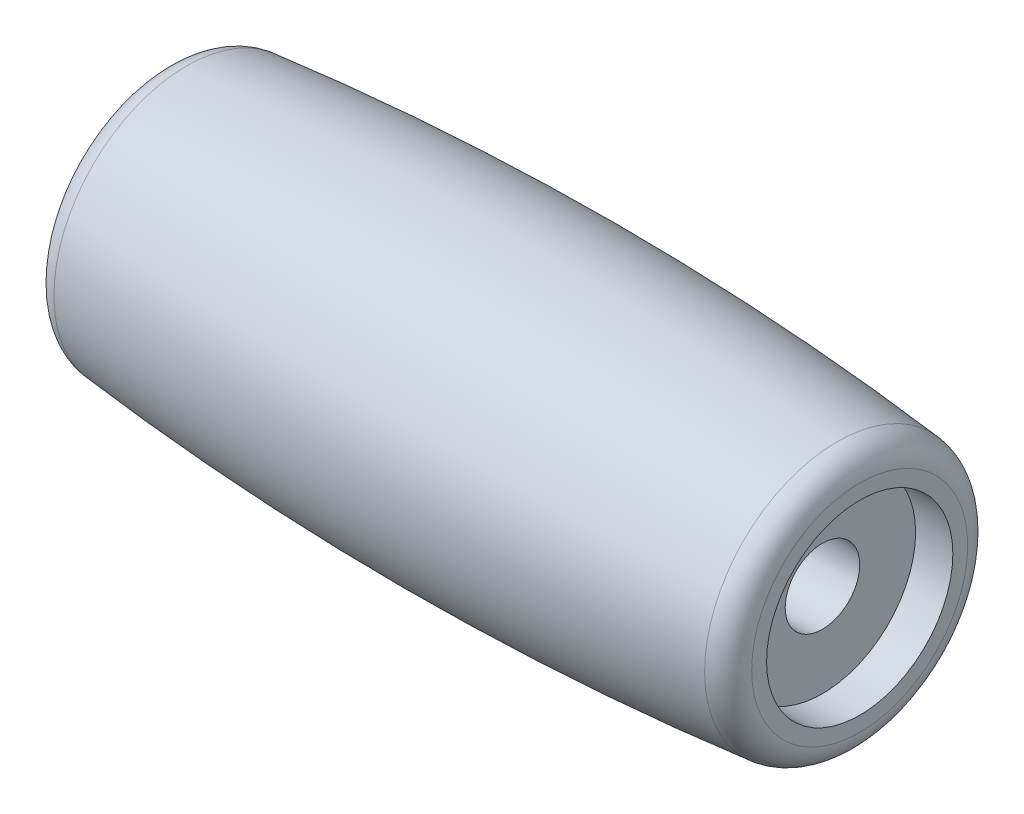
SolidWorks part; units mm, degrees
ref_plane "Front Plane" through (0, 0, 0) normal (0, 0, 1) x (1, 0, 0)
ref_plane "Top Plane" through (0, 0, 0) normal (0, 1, 0) x (1, 0, 0)
ref_plane "Right Plane" through (0, 0, 0) normal (1, 0, 0) x (0, 0, -1)
sketch "Sketch1" plane through (0, 0, 0) normal (0, 0, 1) x (1, 0, 0)
  line L0 (0, 6) -> (0, 0) construction
  line L1 (0, 0) -> (19.3504, 0) construction
  line L2 (-12.5, 1.5) -> (12.5, 1.5)
  line L3 (12.5, 1.5) -> (12.5, 3.75)
  line L4 (12.5, 3.75) -> (14, 3.75)
  line L5 (14, 3.75) -> (14, 4.3486)
  line L6 (-14, 3.75) -> (-14, 4.3486)
  line L7 (-12.5, 3.75) -> (-14, 3.75)
  line L8 (-12.5, 1.5) -> (-12.5, 3.75)
  arc A0 (-13.1, 5.3436) -> (13.1, 5.3436) centre (0, -125.0417) cw
  arc A1 (14, 4.3486) -> (13.1, 5.3436) centre (13, 4.3486) ccw
  arc A2 (-14, 4.3486) -> (-13.1, 5.3436) centre (-13, 4.3486) cw
  point P3 (-19.3504, 0)
  point P14 (0, 1.5)
  point P17 (14, 5.25)
  point P20 (-14, 5.25)
  dimension "D7" = 1
  dimension "D1" = 1.5
  dimension "D2" = 3.75
  dimension "D3" = 1.5
  dimension "D4" = 1.5
  dimension "D5" = 14
  dimension "D6" = 6
revolve "Revolve1" add sketch "Sketch1" angle 360 about L1
